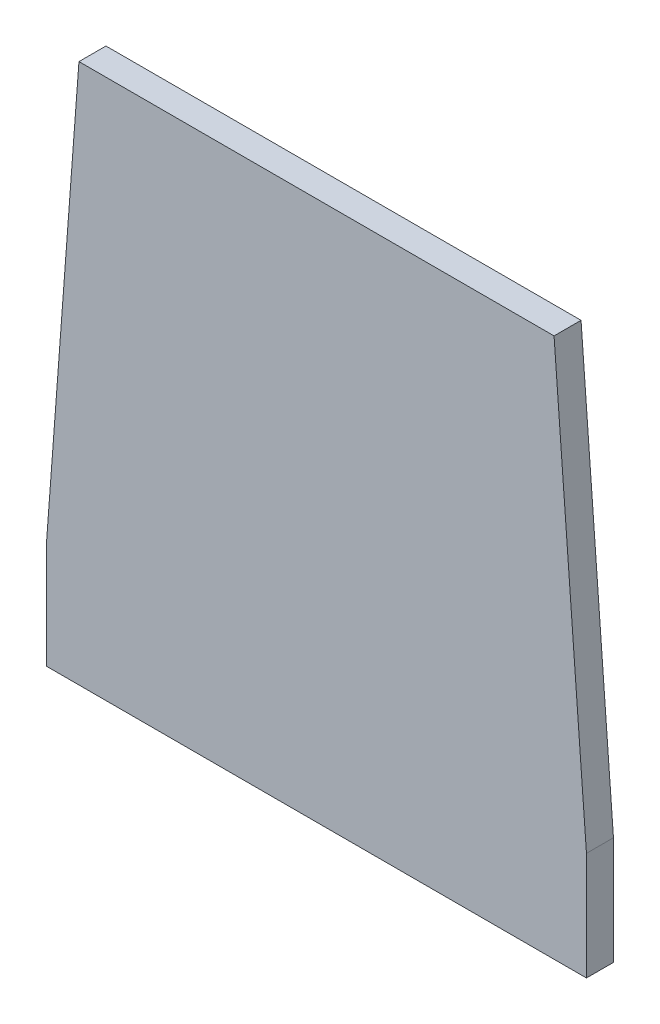
SolidWorks part; units mm, degrees
ref_plane "Front Plane" through (0, 0, 0) normal (0, 0, 1) x (1, 0, 0)
ref_plane "Top Plane" through (0, 0, 0) normal (0, 1, 0) x (1, 0, 0)
ref_plane "Right Plane" through (0, 0, 0) normal (1, 0, 0) x (0, 0, -1)
sketch "Sketch1" plane through (0, 0, 0) normal (0, 0, 1) x (1, 0, 0)
  line L0 (-63.5, -76.2) -> (63.5, -76.2)
  line L1 (-101.6, 101.6) -> (101.6, 101.6) construction
  line L2 (-101.6, 101.6) -> (-101.6, -101.6) construction
  line L3 (-101.6, -101.6) -> (101.6, -101.6) construction
  line L4 (101.6, 101.6) -> (101.6, -101.6) construction
  line L5 (-101.6, 101.6) -> (101.6, -101.6) construction
  line L6 (-101.6, -101.6) -> (101.6, 101.6) construction
  line L7 (63.5, -76.2) -> (63.5, -101.6)
  line L8 (63.5, -101.6) -> (-63.5, -101.6)
  line L9 (-63.5, -101.6) -> (-63.5, -76.2)
  line L10 (-63.5, -76.2) -> (-55.88, 25.4)
  line L11 (-55.88, 25.4) -> (55.88, 25.4)
  line L12 (55.88, 25.4) -> (63.5, -76.2)
  point P0 (0, 0)
  dimension "D1" = 203.2
  dimension "D2" = 203.2
extrude "Boss-Extrude1" add sketch "Sketch1" along normal blind 6.35 contours L12 L11 L10 L0 | L9 L8 L7 L0
sketch "Sketch2" plane through (0, 0, 3.175) normal (0, 0, 1) x (1, 0, 0)
  line L0 (-101.6, -101.6) -> (101.6, -101.6) construction
  line L1 (-101.6, 101.6) -> (-101.6, -101.6) construction
  line L2 (101.6, -101.6) -> (101.6, 101.6) construction
  circle A0 centre (-25.4, -88.9) radius 3.175
  circle A1 centre (25.4, -88.9) radius 3.175
  dimension "D1" = 12.7
  dimension "D2" = 12.7
  dimension "D3" = 6.35
  dimension "D4" = 76.2
  dimension "D5" = 76.2
extrude "Cut-Extrude1" cut sketch "Sketch2" against normal blind 3.175
